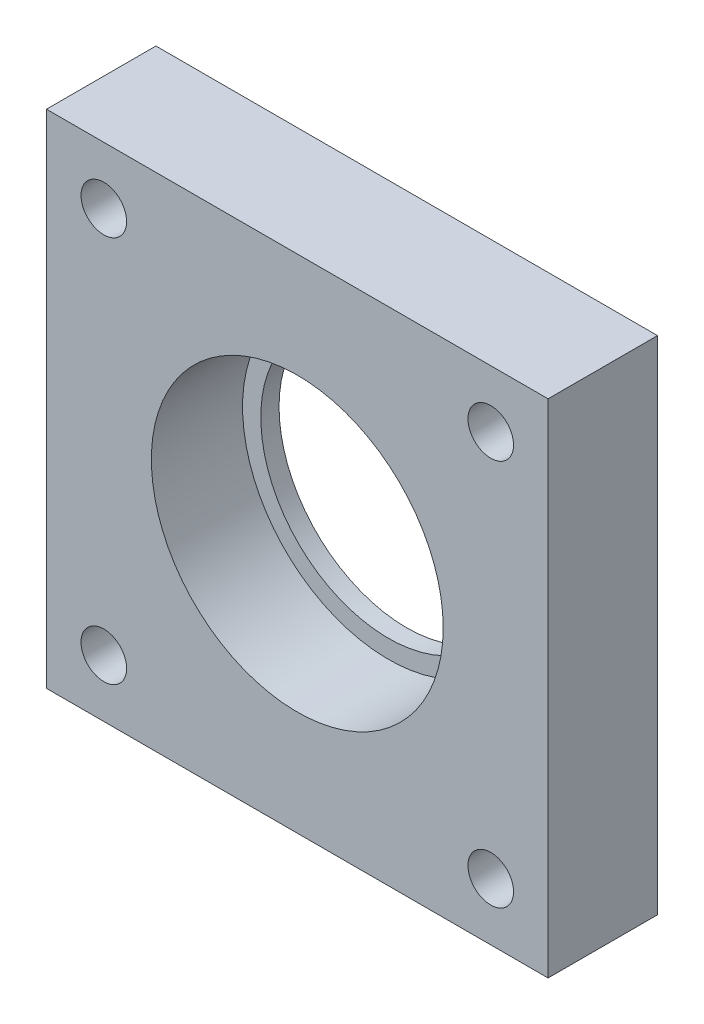
SolidWorks part; units mm, degrees
ref_plane "Piano frontale" through (0, 0, 0) normal (0, 0, 1) x (1, 0, 0)
ref_plane "Piano superiore" through (0, 0, 0) normal (0, 1, 0) x (1, 0, 0)
ref_plane "Piano destro" through (0, 0, 0) normal (1, 0, 0) x (0, 0, -1)
sketch "Schizzo1" plane through (0, 0, 0) normal (0, 0, 1) x (1, 0, 0)
  line L1 (0, 0) -> (55, 0)
  line L2 (0, 0) -> (0, 55)
  line L3 (0, 55) -> (55, 55)
  line L4 (55, 0) -> (55, 55)
  dimension "D1" = 55
  dimension "D2" = 55
extrude "Estrusione-Estrusione1" add sketch "Schizzo1" against normal blind 12
sketch "Schizzo2" plane through (0, 0, 0) normal (0, 0, 1) x (1, 0, 0)
  line L0 (0, 27.5) -> (55, 27.5) construction
  line L1 (0, 55) -> (0, 0) construction
  line L2 (55, 0) -> (55, 55) construction
  circle A0 centre (27.5, 27.5) radius 16
  dimension "D1" = 32
extrude "Taglio-Estrusione1" cut sketch "Schizzo2" against normal blind 10
sketch "Schizzo3" plane through (0, 0, -10) normal (0, 0, 1) x (1, 0, 0)
  line L0 (0, 27.5) -> (55, 27.5) construction
  line L1 (0, 55) -> (0, 0) construction
  line L2 (55, 0) -> (55, 55) construction
  circle A0 centre (27.5, 27.5) radius 14
  dimension "D1" = 28
extrude "Taglio-Estrusione2" cut sketch "Schizzo3" against normal blind 10
sketch "Schizzo4" plane through (0, 0, -12) normal (0, 0, -1) x (-1, 0, 0)
  line L0 (-55, 55) -> (0, 0) construction
  line L1 (-55, 55) -> (0, 55) construction
  line L2 (0, 55) -> (-55, 0) construction
  line L3 (0, 0) -> (-55, 0) construction
  line L4 (-55, 0) -> (-55, 55) construction
  line L5 (-27.5, 27.5) -> (0, 27.5) construction
  line L6 (0, 55) -> (0, 0) construction
  line L7 (-27.5, 27.5) -> (-27.5, 55) construction
  circle A0 centre (-27.5, 27.5) radius 30 construction
  circle A1 centre (-48.7132, 48.7132) radius 2.5
  circle A2 centre (-6.2868, 48.7132) radius 2.5
  circle A3 centre (-48.7132, 6.2868) radius 2.5
  circle A4 centre (-6.2868, 6.2868) radius 2.5
  dimension "D1" = 5
extrude "Taglio-Estrusione3" cut sketch "Schizzo4" against normal through all
